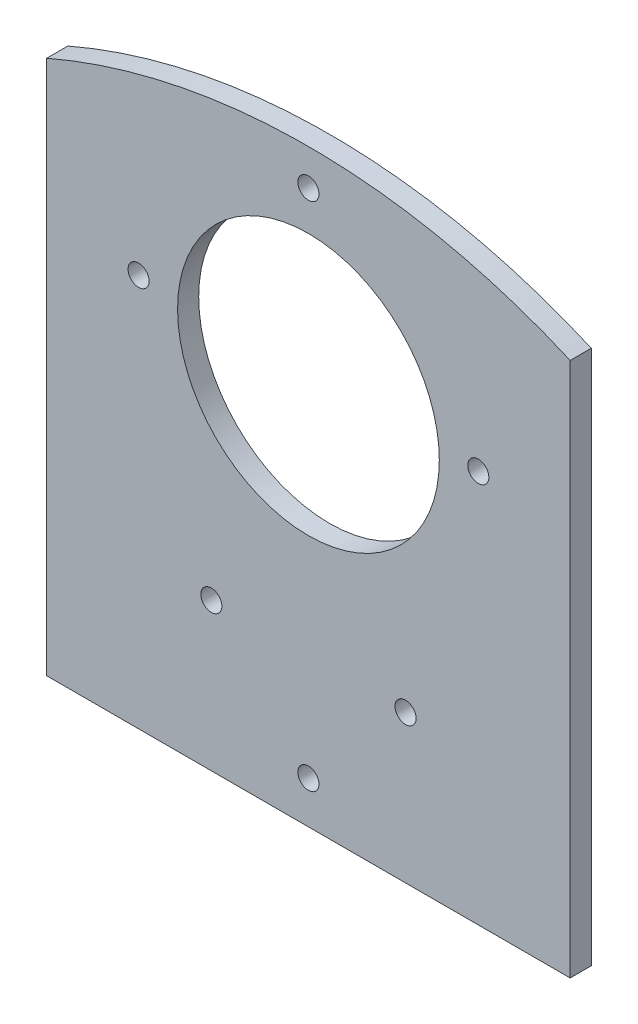
SolidWorks part; units mm, degrees
material "Plain Carbon Steel"
ref_plane "Front Plane" through (0, 0, 0) normal (0, 0, 1) x (1, 0, 0)
ref_plane "Top Plane" through (0, 0, 0) normal (0, 1, 0) x (1, 0, 0)
ref_plane "Right Plane" through (0, 0, 0) normal (1, 0, 0) x (0, 0, -1)
sketch "Sketch1" plane through (0, 0, 0) normal (0, 0, 1) x (1, 0, 0)
  line L1 (35, -52.5) -> (-35, -52.5)
  line L2 (35, -52.5) -> (35, 52.5)
  line L3 (35, 52.5) -> (-35, 52.5)
  line L4 (-35, -52.5) -> (-35, 52.5)
  line L5 (35, -52.5) -> (-35, 52.5) construction
  line L6 (35, 52.5) -> (-35, -52.5) construction
  point P0 (0, 0)
  dimension "D1" = 70
  dimension "D2" = 105
extrude "Boss-Extrude1" add sketch "Sketch1" along normal blind 3
sketch "Sketch2" plane through (0, 0, 0) normal (0, 0, -1) x (-1, 0, 0)
  line L0 (-35, -2.5) -> (35, -2.5) construction
  line L1 (-35, -52.5) -> (-35, 52.5) construction
  line L2 (35, 52.5) -> (35, -52.5) construction
  line L3 (35, -52.5) -> (-35, -52.5) construction
  circle A0 centre (0, 20.5) radius 17.5
  point P11 (0, -2.5)
  dimension "D2" = 35
  dimension "D1" = 50
  dimension "D3" = 23
  dimension "D4" = 35
extrude "Cut-Extrude3" cut sketch "Sketch2" against normal blind 3
sketch "Sketch3" plane through (0, 0, 3) normal (0, 0, 1) x (1, 0, 0)
  circle A5 centre (0, 20.5) radius 17.5 construction
  circle A6 centre (-22.5, 20.5) radius 2
  circle A7 centre (0, 43) radius 2
  circle A8 centre (22.5, 20.5) radius 2
  point P0 (0, 20.5)
  dimension "D2" = 22.5
  dimension "D3" = 22.5
  dimension "D4" = 4
  dimension "D5" = 4
  dimension "D6" = 4
  dimension "D1" = 22.5
sketch "Sketch4" plane through (0, 0, 3) normal (0, 0, 1) x (1, 0, 0)
  line L0 (0, 0) -> (0, -52.5) construction
  line L1 (-35, -52.5) -> (35, -52.5) construction
  circle A0 centre (0, -42.5) radius 2
  circle A1 centre (-23, -17.5) radius 2
  circle A3 centre (23, -17.5) radius 2
  dimension "D3" = 4
  dimension "D1" = 10
  dimension "D2" = 25
  dimension "D4" = 23
sketch "Sketch5" plane through (0, 0, 3) normal (0, 0, 1) x (1, 0, 0)
  line L0 (-35, 40.7935) -> (35, 40.7935) construction
  line L1 (-35, 52.5) -> (-35, -52.5) construction
  line L2 (35, -52.5) -> (35, 52.5) construction
  line L3 (-35, 40.7935) -> (-35, 52.5)
  line L4 (-35, 52.5) -> (35, 52.5)
  line L5 (35, 52.5) -> (35, 40.7935)
  arc A0 (-35, 40.7935) -> (35, 40.7935) centre (0, -39.6661) cw
extrude "Cut-Extrude6" cut sketch "Sketch5" against normal blind 10
scale "Scale1" scale about centroid uniform scaling yes scale factor 1.771429
ref_plane "Plane1" through (0, 0, -1.1571) normal (0, 0, -1) x (-1, 0, 0)
sketch "Sketch6" plane through (0, 0, -1.1571) normal (0, 0, -1) x (-1, 0, 0)
  line L3 (62, -87.3934) -> (62, 77.8695)
  line L4 (-62, 77.8695) -> (-62, -87.3934)
  line L5 (-62, -87.3934) -> (62, -87.3934)
  line L6 (62, -87.3934) -> (62, 77.8695)
  line L7 (-62, 77.8695) -> (-62, -87.3934)
  line L8 (-62, -87.3934) -> (62, -87.3934)
  circle A0 centre (0, 41.9209) radius 31 construction
  arc A1 (62, 77.8695) -> (-62, 77.8695) centre (0, -64.6591) ccw
  arc A2 (62, 77.8695) -> (-62, 77.8695) centre (0, -64.6591) ccw
  circle A3 centre (0, 41.9209) radius 31
  dimension "D1" = 0
extrude "Cut-Extrude7" cut sketch "Sketch6" against normal blind 0.31
sketch "Sketch7" plane through (0, 0, 4.1571) normal (0, 0, 1) x (1, 0, 0)
  line L0 (450, -48.8219) -> (-450, -48.8219) construction
  line L1 (62, -48.8219) -> (-62, -48.8219)
  line L2 (-62, -87.3934) -> (62, -87.3934) construction
  line L3 (-62, 77.8695) -> (-62, -87.3934) construction
  line L4 (62, -87.3934) -> (62, 77.8695) construction
  line L5 (-62, -87.3934) -> (62, -87.3934)
  line L6 (-62, -48.8219) -> (-62, -87.3934)
  line L7 (62, -87.3934) -> (62, -48.8219)
extrude "Cut-Extrude8" cut sketch "Sketch7" against normal blind 10
sketch "Sketch9" plane through (0, 0, 4.1571) normal (0, 0, 1) x (1, 0, 0)
  circle A0 centre (23, -13.8219) radius 2.5
  circle A1 centre (-23, -13.8219) radius 2.5
  circle A2 centre (0, -38.8219) radius 2.5
  dimension "D1" = 5
  dimension "D2" = 5
  dimension "D3" = 5
extrude "Cut-Extrude9" cut sketch "Sketch9" against normal up to surface (5.0043 mm away) up to face at (0, 17.7491, -0.8471)
sketch "Sketch10" plane through (0, 0, 4.1571) normal (0, 0, 1) x (1, 0, 0)
  circle A0 centre (-40.2334, 44.2368) radius 2.5
  circle A1 centre (0, 82.2209) radius 2.5
  circle A2 centre (40.2334, 44.2368) radius 2.5
  dimension "D1" = 5
  dimension "D2" = 5
  dimension "D3" = 5
extrude "Cut-Extrude10" cut sketch "Sketch10" against normal up to surface (5.0043 mm away) up to face at (20.5, -13.8219, -0.8471)
